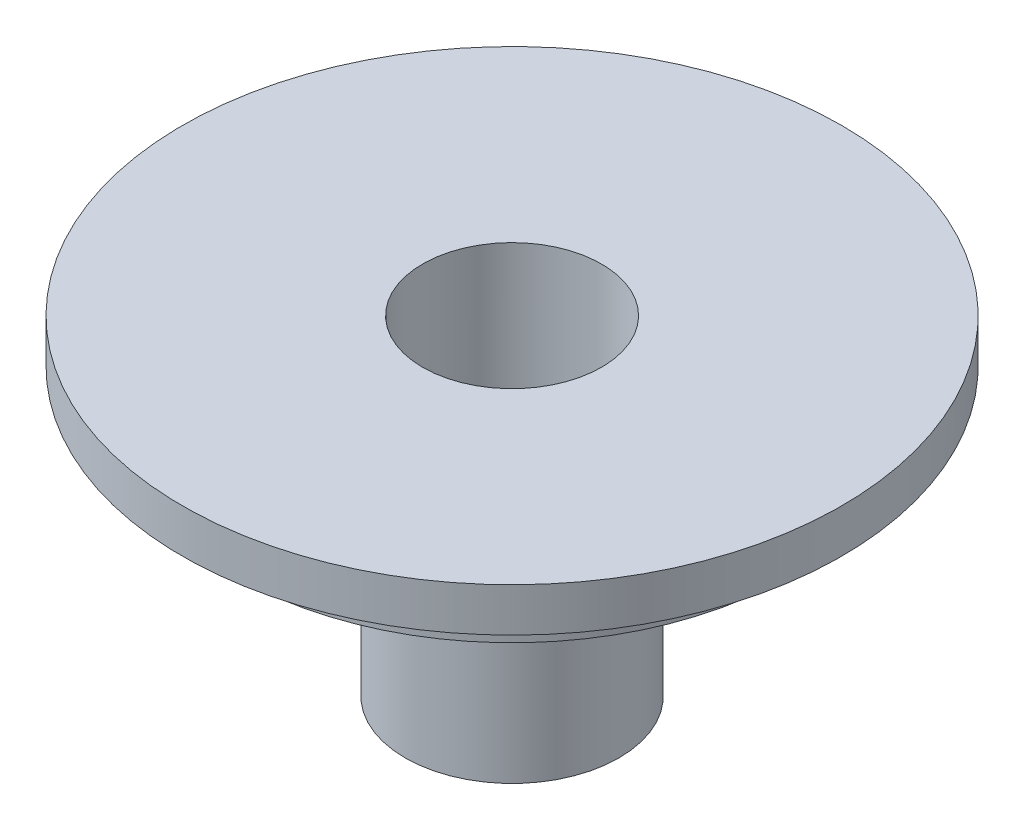
SolidWorks part; units mm, degrees
ref_plane "Front" through (0, 0, 0) normal (0, 0, 1) x (1, 0, 0)
ref_plane "Top" through (0, 0, 0) normal (0, 1, 0) x (1, 0, 0)
ref_plane "Right" through (0, 0, 0) normal (1, 0, 0) x (0, 0, -1)
sketch "Sketch1" plane through (0, 0, 0) normal (0, 0, 1) x (1, 0, 0)
  line L0 (0, 0) -> (0, 20) construction
  line L1 (24.5, 0) -> (24.5, 20)
  line L2 (24.5, 20) -> (75.5, 20)
  line L3 (75.5, 20) -> (75.5, 10)
  line L4 (75.5, 10) -> (64.8397, 10)
  line L5 (64.8397, 10) -> (63.5, 5)
  line L6 (63.5, 5) -> (63.5, 0)
  line L7 (63.5, 0) -> (24.5, 0)
  dimension "D1" = 75.5
  dimension "D2" = 12
  dimension "D3" = 10
  dimension "D4" = 5
  dimension "D5" = 15
  dimension "D6" = 24.5
  dimension "D7" = 20
revolve "Revolve1" add sketch "Sketch1" angle 360 about L0
sketch "Sketch3" plane through (0, 10, 0) normal (0, -1, 0) x (1, 0, 0)
  line L1 (1.5, -73.4847) -> (1.5, -63.5)
  line L2 (1.5, -63.5) -> (-1.5, -63.5)
  line L3 (-1.5, -63.5) -> (-1.5, -73.4847)
  circle A0 centre (0, 0) radius 63.5 construction
  arc A1 (-1.5, -73.4847) -> (1.5, -73.4847) centre (0, 0) ccw
  circle A2 centre (0, 0) radius 75.5 construction
  point P2 (0, -63.5)
  dimension "D1" = 2
  dimension "D2" = 3
extrude "Boss-Extrude1" add sketch "Sketch3" along normal blind 3
sketch "Sketch4" plane through (0, 20, 0) normal (0, 1, 0) x (1, 0, 0)
  circle A0 centre (0, 0) radius 20.5
  circle A1 centre (0, 0) radius 24.5
  circle A2 centre (0, 0) radius 24.5 construction
  dimension "D1" = 41
extrude "Boss-Extrude2" add sketch "Sketch4" against normal offset from surface (10 mm away) 10 up to face at (0, 0, -63.5)
sketch "Sketch5" plane through (0, 0, 0) normal (0, -1, 0) x (1, 0, 0)
  circle A0 centre (0, 0) radius 24.5
  circle A1 centre (0, 0) radius 20.5
  circle A2 centre (0, 0) radius 20.5 construction
  dimension "D1" = 49
extrude "Boss-Extrude3" add sketch "Sketch5" along normal blind 60.5 and the other way through all
sketch "Sketch6" plane through (0, -60.5, 0) normal (0, -1, 0) x (1, 0, 0)
  circle A0 centre (0, 0) radius 23
  dimension "D1" = 46
extrude "Cut-Extrude1" cut sketch "Sketch6" against normal blind 5
sketch "Sketch7" plane through (0, -60.5, 0) normal (0, -1, 0) x (1, 0, 0)
  circle A0 centre (0, 0) radius 47.5937
extrude "Cut-Extrude2" cut sketch "Sketch7" against normal up to surface (5 mm away) up to face at (0, -55.5, -23)
